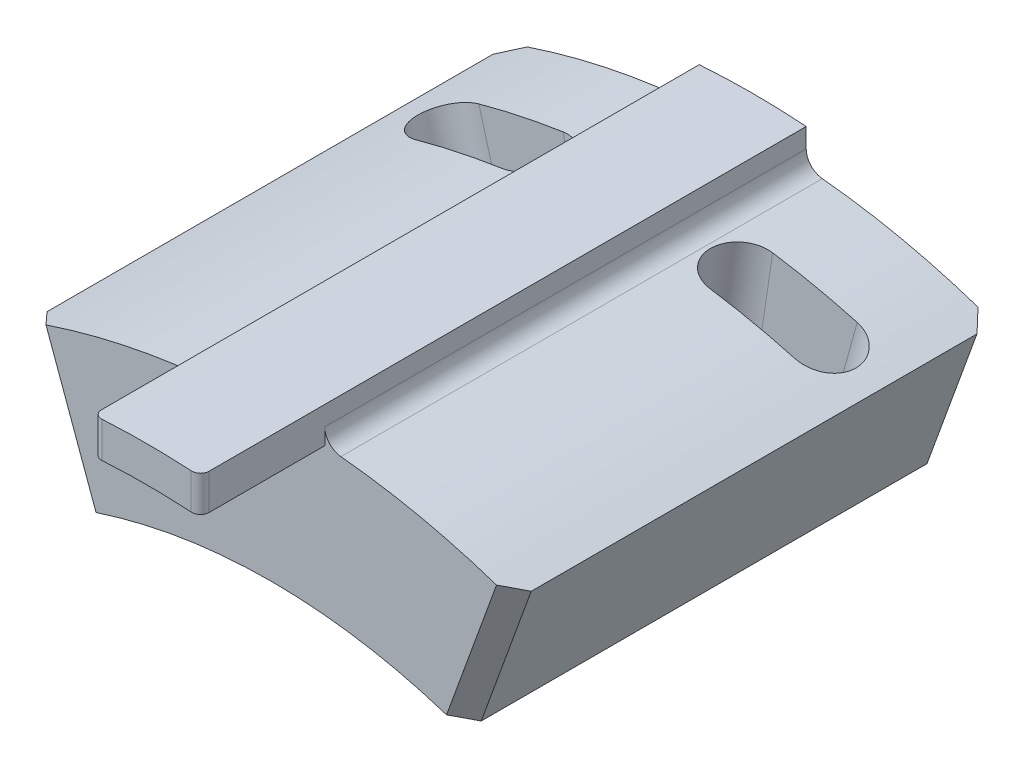
SolidWorks part; units mm, degrees
material "PETG"
ref_plane "Спереди" through (0, 0, 0) normal (0, 0, 1) x (1, 0, 0)
ref_plane "Сверху" through (0, 0, 0) normal (0, 1, 0) x (1, 0, 0)
ref_plane "Справа" through (0, 0, 0) normal (1, 0, 0) x (0, 0, -1)
ref_plane "Плоскость1" through (0, 0, 6.5) normal (0, 0, 1) x (1, 0, 0)
sketch "Эскиз1" plane through (0, 0, 0) normal (0, 0, 1) x (1, 0, 0)
  line L0 (10.7736, 29.6003) -> (13.5782, 37.3058)
  line L1 (-10.7736, 29.6003) -> (-13.5782, 37.3058)
  line L2 (0, 0) -> (0, 84.5239) construction
  line L3 (-3, 41.5919) -> (-3, 39.5865)
  line L4 (3, 41.5919) -> (3, 39.5865)
  arc A0 (10.7736, 29.6003) -> (-10.7736, 29.6003) centre (0, 0) ccw
  arc A1 (3, 41.5919) -> (-3, 41.5919) centre (0, 0) ccw
  arc A2 (13.5782, 37.3058) -> (3, 39.5865) centre (0, 0) ccw
  circle A3 centre (0, 0) radius 41.7 construction
  circle A4 centre (0, 0) radius 31.5 construction
  arc A5 (-3, 39.5865) -> (-13.5782, 37.3058) centre (0, 0) ccw
  arc A7 (13.5782, 37.3058) -> (-13.5782, 37.3058) centre (0, 0) ccw construction
  point P6 (59.769, 18.2732)
  point P7 (70, 0)
  dimension "D1" = 63
  dimension "D4" = 8.2
  dimension "D3" = 20
  dimension "D5" = 6
  dimension "D2" = 10.2
extrude "Бобышка-Вытянуть1" add sketch "Эскиз1" along normal blind 27
sketch "Эскиз2" plane through (0, 0, 27) normal (0, 0, 1) x (1, 0, 0)
  line L0 (3, 39.5865) -> (3, 41.5919) construction
  line L1 (-3, 41.5919) -> (-3, 39.5865) construction
  line L2 (3, 39.5865) -> (3, 41.5919)
  line L3 (-3, 41.5919) -> (-3, 39.5865)
  arc A0 (3, 41.5919) -> (-3, 41.5919) centre (0, 0) ccw construction
  arc A1 (3, 41.5919) -> (-3, 41.5919) centre (0, 0) ccw
  arc A2 (2.8561, 39.5971) -> (-2.8561, 39.5971) centre (0, 0) ccw construction
  arc A6 (3, 39.5865) -> (-3, 39.5865) centre (0, 0) ccw
  dimension "D1" = 2
extrude "Бобышка-Вытянуть2" add sketch "Эскиз2" along normal blind 7
sketch "Эскиз4" plane through (0, 0, 6.5) normal (0, 0, 1) x (1, 0, 0)
  line L0 (0, 0) -> (10.6094, 38.2561) construction
  line L1 (13.7121, 42.8957) -> (8.3673, 23.6231)
  line L4 (8.3673, 23.6231) -> (6.681, 24.0908)
  line L5 (13.7121, 42.8957) -> (12.0257, 43.3634)
  line L6 (6.681, 24.0908) -> (12.0257, 43.3634)
  line L7 (0, 0) -> (0, 31.5) construction
  arc A0 (13.5782, 37.3058) -> (3, 39.5865) centre (0, 0) ccw construction
  arc A1 (10.7736, 29.6003) -> (-10.7736, 29.6003) centre (0, 0) ccw construction
  dimension "D1" = 3.5
  dimension "D2" = 15.5
  dimension "D3" = 25
  dimension "D4" = 20
  dimension "D5" = 1.3648
revolve "Вырез-Повернуть1" cut sketch "Эскиз4" angle 360 about L0
pattern_circular "Круговой массив1" count 2 every 7 about axis through (0, 0, 27) along (0, 0, -1) of "Вырез-Повернуть1"
sketch "Эскиз6" plane through (0, 0, 6.5) normal (0, 0, 1) x (1, 0, 0)
  line L0 (4.656, 31.154) -> (5.868, 39.2639)
  line L1 (8.418, 30.3544) -> (10.6094, 38.2561)
  arc A0 (10.7736, 29.6003) -> (-10.7736, 29.6003) centre (0, 0) ccw construction
  arc A1 (13.5782, 37.3058) -> (3, 39.5865) centre (0, 0) ccw construction
  arc A2 (8.418, 30.3544) -> (4.656, 31.154) centre (0, 0) ccw
  arc A3 (10.6094, 38.2561) -> (5.868, 39.2639) centre (0, 0) ccw
  arc A5 (6.3796, 30.8472) -> (2.918, 31.3646) centre (0, 0) ccw construction
  arc A6 (10.0914, 29.8398) -> (6.7187, 30.7751) centre (0, 0) ccw construction
  arc A10 (7.5931, 38.9671) -> (4.1316, 39.4844) centre (0, 0) ccw construction
  arc A12 (12.2854, 37.7513) -> (8.9127, 38.6866) centre (0, 0) ccw construction
extrude "Вырез-Вытянуть2" cut sketch "Эскиз6" against normal mid plane 3.5
mirror "Зеркальное отражение1" about plane through (0, 0, 0) normal (1, 0, 0) of "Вырез-Вытянуть2", "Круговой массив1", "Вырез-Повернуть1"
fillet "Скругление1" radius 1 2 edges at (-3, 39.5865, 13.5) (3, 39.5865, 13.5)
chamfer "Фаска1" distance 1 angle 45 4 edges at (12.1759, 33.4531, 27) (-12.1759, 33.4531, 27) (-12.1759, 33.4531, 0) (12.1759, 33.4531, 0)
fillet "Скругление2" radius 0.5 2 edges at (3, 40.5892, 34) (-3, 40.5892, 34)
